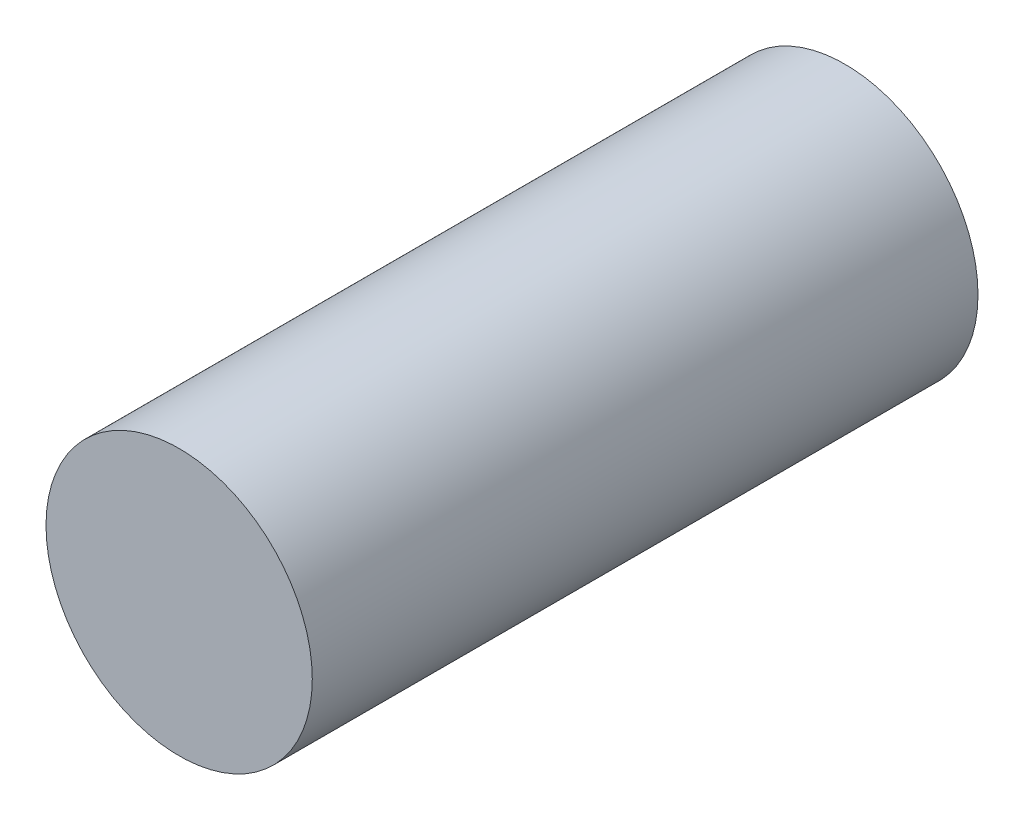
SolidWorks part; units mm, degrees
ref_plane "Front Plane" through (0, 0, 0) normal (0, 0, 1) x (1, 0, 0)
ref_plane "Top Plane" through (0, 0, 0) normal (0, 1, 0) x (1, 0, 0)
ref_plane "Right Plane" through (0, 0, 0) normal (1, 0, 0) x (0, 0, -1)
sketch "Sketch1" plane through (0, 0, 0) normal (0, 0, 1) x (1, 0, 0)
  circle A0 centre (0, 0) radius 4
  dimension "D1" = 8
extrude "Boss-Extrude1" add sketch "Sketch1" along normal blind 20
